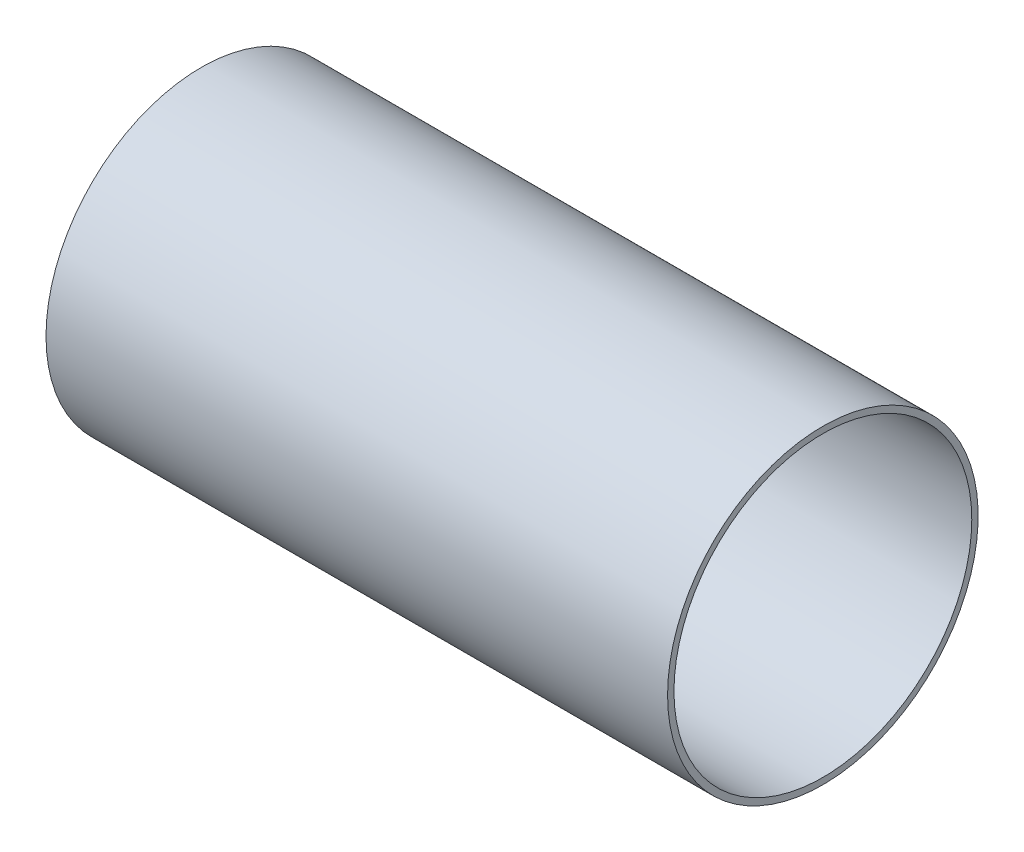
SolidWorks part; units mm, degrees
ref_plane "Front Plane" through (0, 0, 0) normal (1, 0, 0) x (0, 1, 0)
ref_plane "Top Plane" through (0, 0, 0) normal (0, 0, 1) x (0, 1, 0)
ref_plane "Right Plane" through (0, 0, 0) normal (0, 1, 0) x (-1, 0, 0)
sketch "Sketch1" plane through (0, 0, 0) normal (1, 0, 0) x (0, 1, 0)
  circle A0 centre (0, 0) radius 36.5125
  circle A1 centre (0, 0) radius 38.0746
  dimension "D1" = 73.025
  dimension "D2" = 76.1492
extrude "Boss-Extrude1" add sketch "Sketch1" along normal blind 152.4
